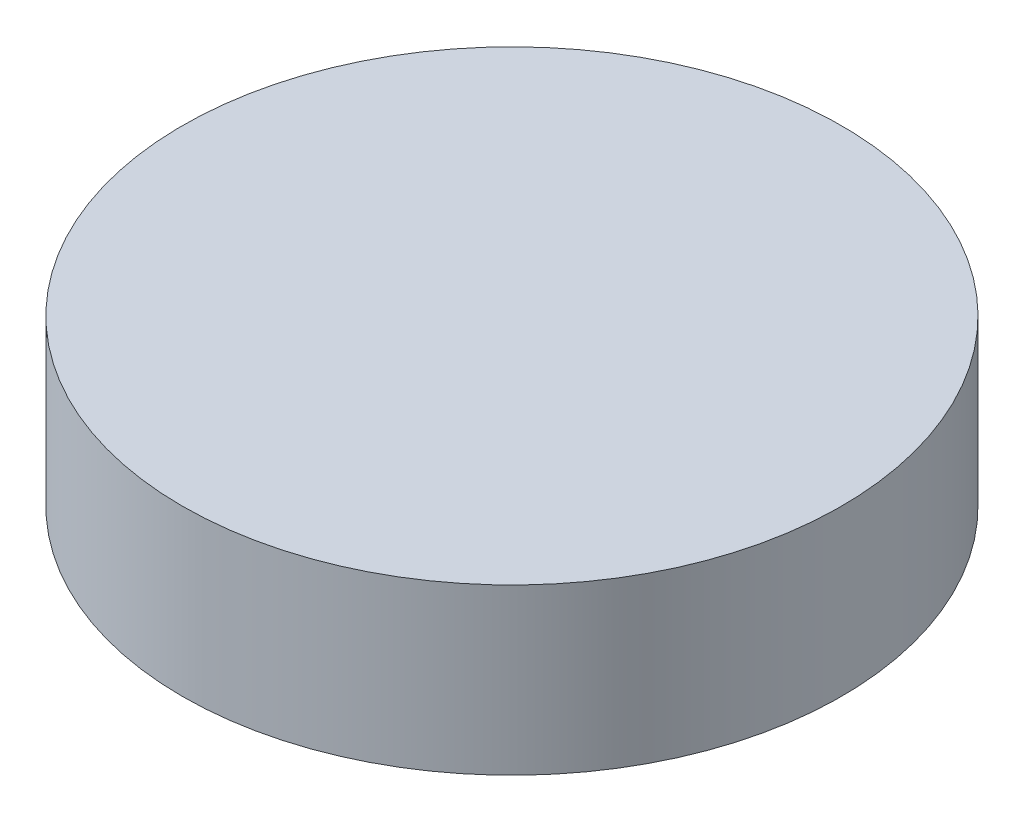
SolidWorks part; units mm, degrees
material "Nickel"
ref_plane "Front Plane" through (0, 0, 0) normal (0, 0, 1) x (1, 0, 0)
ref_plane "Top Plane" through (0, 0, 0) normal (0, 1, 0) x (1, 0, 0)
ref_plane "Right Plane" through (0, 0, 0) normal (1, 0, 0) x (0, 0, -1)
sketch "Sketch1" plane through (0, 0, 0) normal (0, 1, 0) x (1, 0, 0)
  circle A0 centre (0, 0) radius 3.175
  dimension "D1" = 6.35
extrude "Boss-Extrude1" add sketch "Sketch1" along normal blind 1.5875
